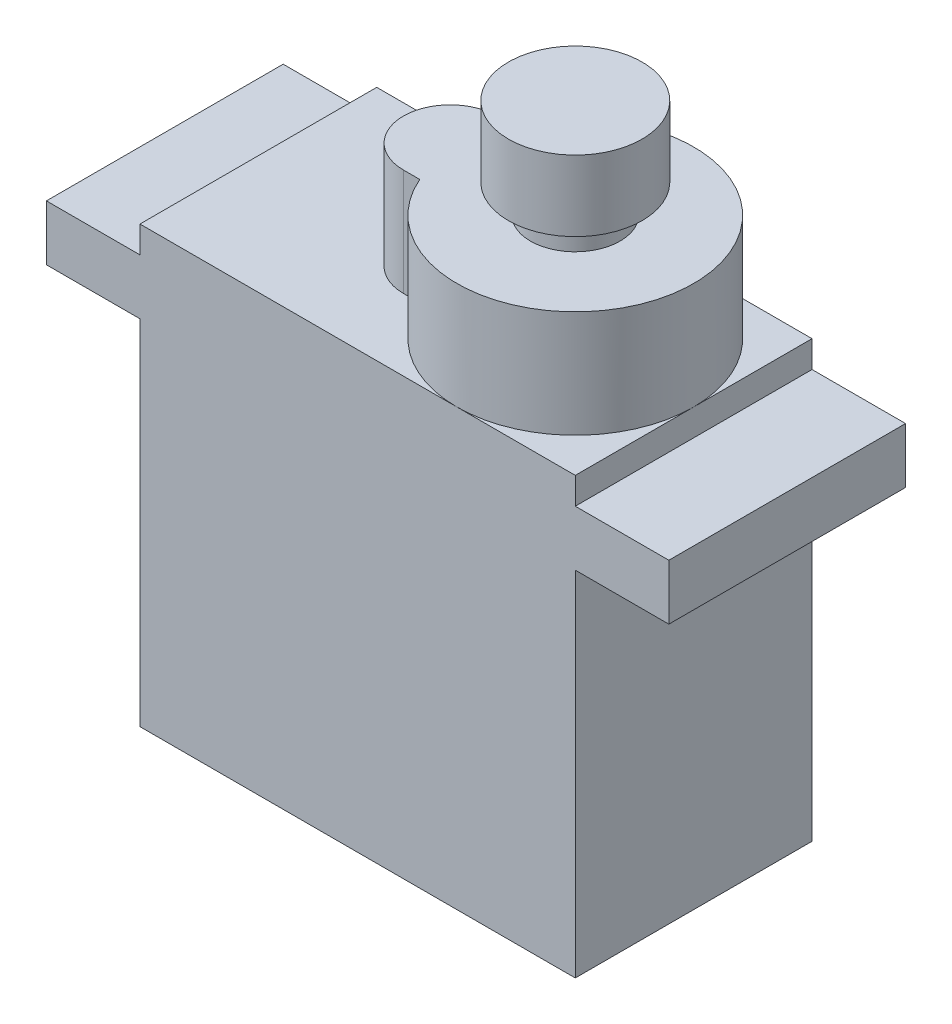
SolidWorks part; units mm, degrees
ref_plane "Plan de face" through (0, 0, 0) normal (0, 0, 1) x (1, 0, 0)
ref_plane "Plan de dessus" through (0, 0, 0) normal (0, 1, 0) x (1, 0, 0)
ref_plane "Plan de droite" through (0, 0, 0) normal (1, 0, 0) x (0, 0, -1)
sketch "Esquisse1" plane through (0, 0, 0) normal (0, 0, 1) x (1, 0, 0)
  line L0 (-11.4, 10) -> (-16.3, 10)
  line L1 (-11.4, 11.4) -> (11.4, 11.4)
  line L2 (-11.4, 11.4) -> (-11.4, 10)
  line L3 (-11.4, -11.4) -> (11.4, -11.4)
  line L4 (11.4, 11.4) -> (11.4, 10)
  line L5 (-11.4, 11.4) -> (11.4, -11.4) construction
  line L6 (-11.4, -11.4) -> (11.4, 11.4) construction
  line L7 (-16.3, 10) -> (-16.3, 7.1)
  line L8 (-16.3, 7.1) -> (-11.4, 7.1)
  line L9 (11.4, 10) -> (16.3, 10)
  line L10 (16.3, 10) -> (16.3, 7.1)
  line L11 (16.3, 7.1) -> (11.4, 7.1)
  line L12 (-11.4, 7.1) -> (-11.4, -11.4)
  line L13 (11.4, 7.1) -> (11.4, -11.4)
  point P0 (0, 0)
  dimension "D1" = 22.8
  dimension "D2" = 22.8
  dimension "D3" = 18.5
  dimension "D4" = 4.9
  dimension "D5" = 2.9
extrude "Boss.-Extru.1" add sketch "Esquisse1" along normal blind 12.4
sketch "Esquisse2" plane through (0, 11.4, 0) normal (0, 1, 0) x (1, 0, 0)
  line L0 (-1.35, -3.75) -> (-0.4954, -3.75)
  line L1 (-1.35, -8.65) -> (-0.4954, -8.65)
  line L2 (11.4, 0) -> (-11.4, 0) construction
  line L3 (11.4, -12.4) -> (-11.4, -12.4) construction
  line L4 (11.4, -12.4) -> (11.4, 0) construction
  line L5 (5.2, -6.2) -> (-1.35, -6.2) construction
  line L7 (-1.35, -6.2) -> (-3.8, -6.2) construction
  arc A1 (-0.4954, -8.65) -> (-0.4954, -3.75) centre (5.2, -6.2) ccw
  arc A2 (-1.35, -3.75) -> (-1.35, -8.65) centre (-1.35, -6.2) ccw
  point P4 (0, 0)
  point P13 (0.6451, -6.2)
  point P16 (0, 0)
  point P17 (-1.2427, -6.2)
  dimension "D1" = 4.9
  dimension "D2" = 9
extrude "Boss.-Extru.2" add sketch "Esquisse2" along normal blind 5.6
sketch "Esquisse3" plane through (0, 17, 0) normal (0, 1, 0) x (1, 0, 0)
  circle A0 centre (5.2, -6.2) radius 2.35
  dimension "D1" = 4.7
extrude "Boss.-Extru.3" add sketch "Esquisse3" along normal blind 5.2
sketch "Esquisse4" plane through (0, 22.2, 0) normal (0, 1, 0) x (1, 0, 0)
  circle A0 centre (5.2, -6.2) radius 3.5
  dimension "D1" = 7
extrude "Boss.-Extru.4" add sketch "Esquisse4" against normal blind 3.7
